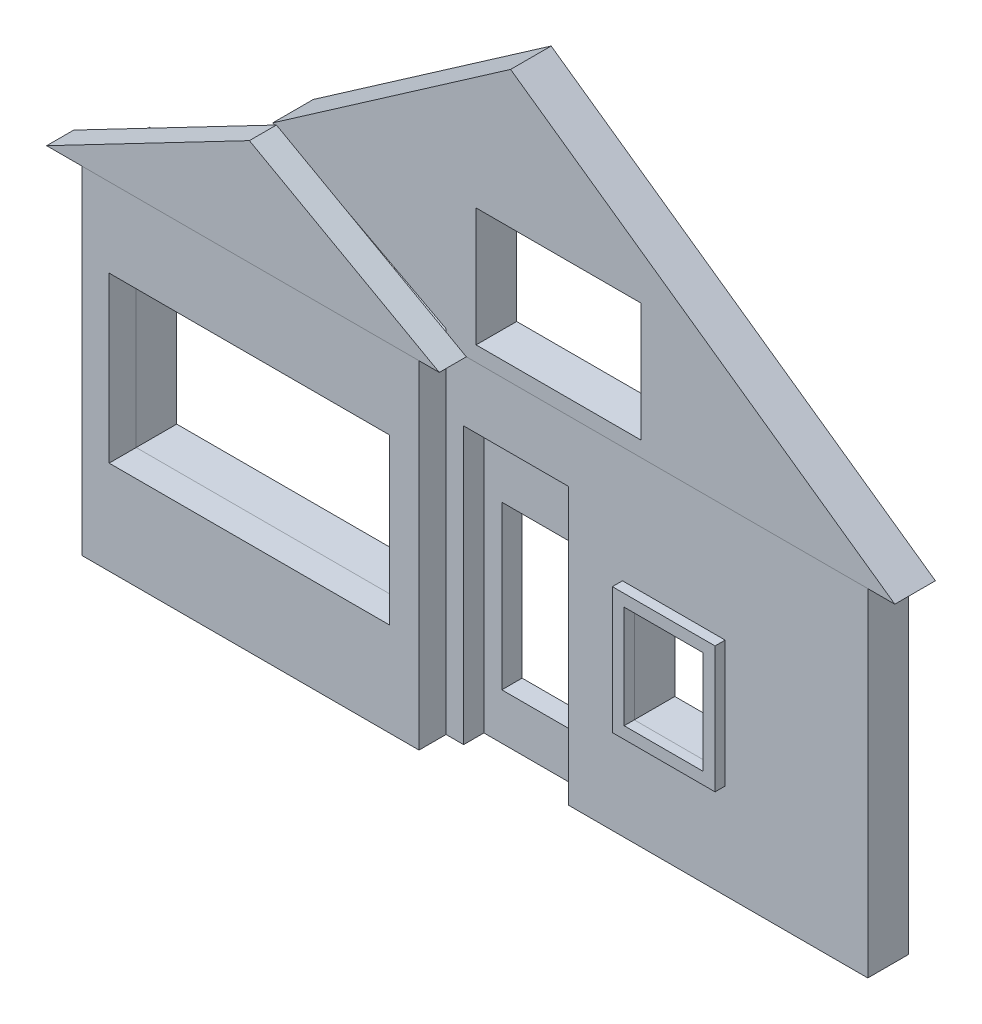
SolidWorks part; units mm, degrees
ref_plane "Front Plane" through (0, 0, 0) normal (0, 0, 1) x (1, 0, 0)
ref_plane "Top Plane" through (0, 0, 0) normal (0, 1, 0) x (1, 0, 0)
ref_plane "Right Plane" through (0, 0, 0) normal (1, 0, 0) x (0, 0, -1)
sketch "WallSketch" plane through (0, 0, 0) normal (0, 0, 1) x (1, 0, 0)
  line L1 (-112.25, -49.9) -> (112.25, -49.9)
  line L2 (-112.25, -49.9) -> (-112.25, 49.9)
  line L3 (-112.25, 49.9) -> (112.25, 49.9)
  line L4 (112.25, -49.9) -> (112.25, 49.9)
  line L5 (-112.25, -49.9) -> (112.25, 49.9) construction
  line L6 (-112.25, 49.9) -> (112.25, -49.9) construction
  point P0 (0, 0)
  dimension "Width" = 224.5
  dimension "Height" = 99.8
extrude "MainWall" add sketch "WallSketch" along normal mid plane 12
sketch "WindowSketch" plane through (0, 0, 6) normal (0, 0, 1) x (1, 0, 0)
  line L1 (43.15, -18.3) -> (66.55, -18.3)
  line L2 (43.15, -18.3) -> (43.15, 12.1)
  line L3 (43.15, 12.1) -> (66.55, 12.1)
  line L4 (66.55, -18.3) -> (66.55, 12.1)
  line L5 (43.15, -18.3) -> (66.55, 12.1) construction
  line L6 (43.15, 12.1) -> (66.55, -18.3) construction
  point P0 (54.85, -3.1)
  dimension "WindowWidth" = 23.4
  dimension "WindowHeight" = 30.4
  dimension "CenterX" = 54.85
  dimension "CenterY" = 3.1
extrude "WindowCut" cut sketch "WindowSketch" against normal blind 12.2
sketch "Pilot001_EntranceRecessSketch" plane through (0, 0, 0) normal (0, 0, 1) x (1, 0, 0)
  line L0 (-7.35, -49.9) -> (23.65, -49.9)
  line L1 (23.65, -49.9) -> (23.65, 31.8)
  line L2 (23.65, 31.8) -> (-7.35, 31.8)
  line L3 (-7.35, 31.8) -> (-7.35, -49.9)
  dimension "L0V0X" = 7.35
  dimension "L0V0Y" = 49.9
  dimension "L0V1X" = 23.65
  dimension "L0V1Y" = 49.9
  dimension "L0V2X" = 23.65
  dimension "L0V2Y" = 31.8
  dimension "L0V3X" = 7.35
  dimension "L0V3Y" = 31.8
extrude "Pilot001_EntranceRecess_PROVISIONAL" cut sketch "Pilot001_EntranceRecessSketch" against normal blind 6 from offset 6
sketch "Pilot001_DoorOpeningSketch" plane through (0, 0, 0) normal (0, 0, 1) x (1, 0, 0)
  line L0 (-2.05, -36.2) -> (18.85, -36.2)
  line L1 (18.85, -36.2) -> (18.85, 11.9)
  line L2 (18.85, 11.9) -> (-2.05, 11.9)
  line L3 (-2.05, 11.9) -> (-2.05, -36.2)
  dimension "L0V0X" = 2.05
  dimension "L0V0Y" = 36.2
  dimension "L0V1X" = 18.85
  dimension "L0V1Y" = 36.2
  dimension "L0V2X" = 18.85
  dimension "L0V2Y" = 11.9
  dimension "L0V3X" = 2.05
  dimension "L0V3Y" = 11.9
extrude "Pilot001_DoorOpening_PROVISIONAL" cut sketch "Pilot001_DoorOpeningSketch" against normal blind 6.2
sketch "Pilot001_LargeWindowOpeningSketch" plane through (0, 0, 0) normal (0, 0, 1) x (1, 0, 0)
  line L0 (-104.25, -22.2) -> (-21.35, -22.2)
  line L1 (-21.35, -22.2) -> (-21.35, 26.5)
  line L2 (-21.35, 26.5) -> (-104.25, 26.5)
  line L3 (-104.25, 26.5) -> (-104.25, -22.2)
  dimension "L0V0X" = 104.25
  dimension "L0V0Y" = 22.2
  dimension "L0V1X" = 21.35
  dimension "L0V1Y" = 22.2
  dimension "L0V2X" = 21.35
  dimension "L0V2Y" = 26.5
  dimension "L0V3X" = 104.25
  dimension "L0V3Y" = 26.5
extrude "Pilot001_LargeWindowOpening_PROVISIONAL" cut sketch "Pilot001_LargeWindowOpeningSketch" against normal blind 12.2 from offset 6
sketch "Pilot001_LeftBayBaseSketch" plane through (0, 0, 0) normal (0, 0, 1) x (1, 0, 0)
  line L0 (-112.25, -49.9) -> (-12.55, -49.9)
  line L1 (-12.55, -49.9) -> (-12.55, -22.2)
  line L2 (-12.55, -22.2) -> (-112.25, -22.2)
  line L3 (-112.25, -22.2) -> (-112.25, -49.9)
  dimension "L0V0Y" = 49.9
  dimension "L0V1Y" = 49.9
  dimension "L0V0X" = 112.25
  dimension "L0V1X" = 12.55
  dimension "L0V2X" = 12.55
  dimension "L0V2Y" = 22.2
  dimension "L0V3X" = 112.25
  dimension "L0V3Y" = 22.2
extrude "Pilot001_LeftBayBase_PROVISIONAL" add sketch "Pilot001_LeftBayBaseSketch" along normal blind 8 from offset 6 separate body
sketch "Pilot001_LeftBayUpperSupportSketch" plane through (0, 0, 0) normal (0, 0, 1) x (1, 0, 0)
  line L0 (-112.25, -22.2) -> (-104.25, -22.2)
  line L1 (-104.25, -22.2) -> (-104.25, 26.5)
  line L2 (-104.25, 26.5) -> (-21.35, 26.5)
  line L3 (-21.35, 26.5) -> (-21.35, -22.2)
  line L4 (-21.35, -22.2) -> (-12.55, -22.2)
  line L5 (-12.55, -22.2) -> (-12.55, 49.9)
  line L6 (-12.55, 49.9) -> (-112.25, 49.9)
  line L7 (-112.25, 49.9) -> (-112.25, -22.2)
  dimension "L0V0Y" = 22.2
  dimension "L0V1Y" = 22.2
  dimension "L0V2Y" = 26.5
  dimension "L0V3Y" = 26.5
  dimension "L0V0X" = 112.25
  dimension "L0V1X" = 104.25
  dimension "L0V2X" = 104.25
  dimension "L0V3X" = 21.35
  dimension "L0V4X" = 21.35
  dimension "L0V4Y" = 22.2
  dimension "L0V5X" = 12.55
  dimension "L0V5Y" = 22.2
  dimension "L0V6X" = 12.55
  dimension "L0V6Y" = 49.9
  dimension "L0V7X" = 112.25
  dimension "L0V7Y" = 49.9
extrude "Pilot001_LeftBayUpperSupport_PROVISIONAL" add sketch "Pilot001_LeftBayUpperSupportSketch" along normal blind 8 from offset 6
sketch "Pilot001_MainGableProfileSketch" plane through (0, 0, 0) normal (0, 0, 1) x (1, 0, 0)
  line L0 (-12.55, 49.9) -> (120.25, 49.9)
  line L1 (120.25, 49.9) -> (6.55, 130.1)
  line L2 (6.55, 130.1) -> (-63.85, 81.2)
  line L3 (-63.85, 81.2) -> (-12.55, 54.1)
  line L4 (-12.55, 54.1) -> (-12.55, 49.9)
  dimension "L0V0Y" = 49.9
  dimension "L0V1Y" = 49.9
  dimension "L0V0X" = 12.55
  dimension "L0V1X" = 120.25
  dimension "L0V2X" = 6.55
  dimension "L0V2Y" = 130.1
  dimension "L0V3X" = 63.85
  dimension "L0V3Y" = 81.2
  dimension "L0V4X" = 12.55
  dimension "L0V4Y" = 54.1
extrude "Pilot001_MainGableProfile_PROVISIONAL" add sketch "Pilot001_MainGableProfileSketch" against normal blind 12 from offset 6 separate body
sketch "Pilot001_LeftGableProfileSketch" plane through (0, 0, 0) normal (0, 0, 1) x (1, 0, 0)
  line L0 (-122.75, 49.9) -> (-6.55, 49.9)
  line L1 (-6.55, 49.9) -> (-62.75, 81.2)
  line L2 (-62.75, 81.2) -> (-122.75, 49.9)
  dimension "L0V0Y" = 49.9
  dimension "L0V1Y" = 49.9
  dimension "L0V0X" = 122.75
  dimension "L0V1X" = 6.55
  dimension "L0V2X" = 62.75
  dimension "L0V2Y" = 81.2
extrude "Pilot001_LeftGableProfile_PROVISIONAL" add sketch "Pilot001_LeftGableProfileSketch" along normal blind 8 from offset 6 separate body
sketch "Pilot001_UpperGableWindowOpeningSketch" plane through (0, 0, 0) normal (0, 0, 1) x (1, 0, 0)
  line L0 (-3.65, 54.4) -> (45.15, 54.4)
  line L1 (45.15, 54.4) -> (45.15, 89.5)
  line L2 (45.15, 89.5) -> (-3.65, 89.5)
  line L3 (-3.65, 89.5) -> (-3.65, 54.4)
  dimension "L0V0X" = 3.65
  dimension "L0V0Y" = 54.4
  dimension "L0V1X" = 45.15
  dimension "L0V1Y" = 54.4
  dimension "L0V2X" = 45.15
  dimension "L0V2Y" = 89.5
  dimension "L0V3X" = 3.65
  dimension "L0V3Y" = 89.5
extrude "Pilot001_UpperGableWindowOpening_PROVISIONAL" cut sketch "Pilot001_UpperGableWindowOpeningSketch" against normal blind 12.2 from offset 6
sketch "Pilot001_OpeningSurroundSketch" plane through (0, 0, 0) normal (0, 0, 1) x (1, 0, 0)
  line L0 (39.65, -21.8) -> (70.05, -21.8)
  line L1 (70.05, -21.8) -> (70.05, 15.6)
  line L2 (70.05, 15.6) -> (39.65, 15.6)
  line L3 (39.65, 15.6) -> (39.65, -21.8)
  line L4 (43.15, -18.3) -> (66.55, -18.3)
  line L5 (66.55, -18.3) -> (66.55, 12.1)
  line L6 (66.55, 12.1) -> (43.15, 12.1)
  line L7 (43.15, 12.1) -> (43.15, -18.3)
  dimension "L0V0X" = 39.65
  dimension "L0V0Y" = 21.8
  dimension "L0V1X" = 70.05
  dimension "L0V1Y" = 21.8
  dimension "L0V2X" = 70.05
  dimension "L0V2Y" = 15.6
  dimension "L0V3X" = 39.65
  dimension "L0V3Y" = 15.6
  dimension "L1V0X" = 43.15
  dimension "L1V0Y" = 18.3
  dimension "L1V1X" = 66.55
  dimension "L1V1Y" = 18.3
  dimension "L1V2X" = 66.55
  dimension "L1V2Y" = 12.1
  dimension "L1V3X" = 43.15
  dimension "L1V3Y" = 12.1
extrude "Pilot001_OpeningSurround_PROVISIONAL" add sketch "Pilot001_OpeningSurroundSketch" along normal blind 3 from offset 6 separate body
equation "\"FacadeWidth\" = 224.5mm"
equation "\"WallHeight\" = 99.8mm"
equation "\"BackingThickness\" = 12mm"
equation "\"ArchitecturalHeight\" = 180mm"
equation "\"BayWidth\" = 99.7mm"
equation "\"BaseHeight\" = 27.7mm"
equation "\"BayProjection\" = 8mm"
equation "\"LargeLeft\" = 8mm"
equation "\"LargeRight\" = 90.9mm"
equation "\"LargeHead\" = 76.4mm"
equation "\"EntranceLeft\" = 104.9mm"
equation "\"EntranceRight\" = 135.9mm"
equation "\"EntranceHead\" = 81.7mm"
equation "\"RecessDepth\" = 6mm"
equation "\"DoorLeft\" = 110.2mm"
equation "\"DoorRight\" = 131.1mm"
equation "\"DoorBottom\" = 13.7mm"
equation "\"DoorHead\" = 61.8mm"
equation "\"RightLeft\" = 155.4mm"
equation "\"RightRight\" = 178.8mm"
equation "\"RightBottom\" = 31.6mm"
equation "\"RightHead\" = 62mm"
equation "\"UpperLeft\" = 108.6mm"
equation "\"UpperRight\" = 157.4mm"
equation "\"UpperBottom\" = 104.3mm"
equation "\"UpperHead\" = 139.4mm"
equation "\"BorderLeft\" = 3.5mm"
equation "\"BorderRight\" = 3.5mm"
equation "\"BorderTop\" = 3.5mm"
equation "\"BorderBottom\" = 3.5mm"
equation "\"SurroundProjection\" = 3mm"
equation "\"MainRoofRight\" = 232.5mm"
equation "\"MainRidgeX\" = 118.8mm"
equation "\"RoofJunctionX\" = 48.4mm"
equation "\"LowerRidge\" = 131.1mm"
equation "\"RoofJunctionY\" = 104mm"
equation "\"LeftRoofLeft\" = -10.5mm"
equation "\"LeftRoofRight\" = 105.7mm"
equation "\"LeftRidgeX\" = 49.5mm"
equation "\"CutTolerance\" = 0.2mm"
equation "\"Width@WallSketch\" = \"FacadeWidth\""
equation "\"Height@WallSketch\" = \"WallHeight\""
equation "\"D1@MainWall\" = \"BackingThickness\""
equation "\"WindowWidth@WindowSketch\" = \"RightRight\" - \"RightLeft\""
equation "\"WindowHeight@WindowSketch\" = \"RightHead\" - \"RightBottom\""
equation "\"CenterX@WindowSketch\" = abs((\"RightLeft\" + \"RightRight\") / 2 - \"FacadeWidth\" / 2)"
equation "\"CenterY@WindowSketch\" = abs((\"RightBottom\" + \"RightHead\") / 2 - \"WallHeight\" / 2)"
equation "\"L0V0X@Pilot001_EntranceRecessSketch\" = abs((\"EntranceLeft\"-(\"FacadeWidth\"/2)))"
equation "\"L0V0Y@Pilot001_EntranceRecessSketch\" = abs((0mm-(\"WallHeight\"/2)))"
equation "\"L0V1X@Pilot001_EntranceRecessSketch\" = abs((\"EntranceRight\"-(\"FacadeWidth\"/2)))"
equation "\"L0V1Y@Pilot001_EntranceRecessSketch\" = abs((0mm-(\"WallHeight\"/2)))"
equation "\"L0V2X@Pilot001_EntranceRecessSketch\" = abs((\"EntranceRight\"-(\"FacadeWidth\"/2)))"
equation "\"L0V2Y@Pilot001_EntranceRecessSketch\" = abs((\"EntranceHead\"-(\"WallHeight\"/2)))"
equation "\"L0V3X@Pilot001_EntranceRecessSketch\" = abs((\"EntranceLeft\"-(\"FacadeWidth\"/2)))"
equation "\"L0V3Y@Pilot001_EntranceRecessSketch\" = abs((\"EntranceHead\"-(\"WallHeight\"/2)))"
equation "\"Depth@Pilot001_EntranceRecess_PROVISIONAL\" = \"RecessDepth\""
equation "\"L0V0X@Pilot001_DoorOpeningSketch\" = abs((\"DoorLeft\"-(\"FacadeWidth\"/2)))"
equation "\"L0V0Y@Pilot001_DoorOpeningSketch\" = abs((\"DoorBottom\"-(\"WallHeight\"/2)))"
equation "\"L0V1X@Pilot001_DoorOpeningSketch\" = abs((\"DoorRight\"-(\"FacadeWidth\"/2)))"
equation "\"L0V1Y@Pilot001_DoorOpeningSketch\" = abs((\"DoorBottom\"-(\"WallHeight\"/2)))"
equation "\"L0V2X@Pilot001_DoorOpeningSketch\" = abs((\"DoorRight\"-(\"FacadeWidth\"/2)))"
equation "\"L0V2Y@Pilot001_DoorOpeningSketch\" = abs((\"DoorHead\"-(\"WallHeight\"/2)))"
equation "\"L0V3X@Pilot001_DoorOpeningSketch\" = abs((\"DoorLeft\"-(\"FacadeWidth\"/2)))"
equation "\"L0V3Y@Pilot001_DoorOpeningSketch\" = abs((\"DoorHead\"-(\"WallHeight\"/2)))"
equation "\"Depth@Pilot001_DoorOpening_PROVISIONAL\" = ((\"BackingThickness\"-\"RecessDepth\")+\"CutTolerance\")"
equation "\"L0V0X@Pilot001_LargeWindowOpeningSketch\" = abs((\"LargeLeft\"-(\"FacadeWidth\"/2)))"
equation "\"L0V0Y@Pilot001_LargeWindowOpeningSketch\" = abs((\"BaseHeight\"-(\"WallHeight\"/2)))"
equation "\"L0V1X@Pilot001_LargeWindowOpeningSketch\" = abs((\"LargeRight\"-(\"FacadeWidth\"/2)))"
equation "\"L0V1Y@Pilot001_LargeWindowOpeningSketch\" = abs((\"BaseHeight\"-(\"WallHeight\"/2)))"
equation "\"L0V2X@Pilot001_LargeWindowOpeningSketch\" = abs((\"LargeRight\"-(\"FacadeWidth\"/2)))"
equation "\"L0V2Y@Pilot001_LargeWindowOpeningSketch\" = abs((\"LargeHead\"-(\"WallHeight\"/2)))"
equation "\"L0V3X@Pilot001_LargeWindowOpeningSketch\" = abs((\"LargeLeft\"-(\"FacadeWidth\"/2)))"
equation "\"L0V3Y@Pilot001_LargeWindowOpeningSketch\" = abs((\"LargeHead\"-(\"WallHeight\"/2)))"
equation "\"Depth@Pilot001_LargeWindowOpening_PROVISIONAL\" = (\"BackingThickness\"+\"CutTolerance\")"
equation "\"L0V0X@Pilot001_LeftBayBaseSketch\" = abs((0mm-(\"FacadeWidth\"/2)))"
equation "\"L0V0Y@Pilot001_LeftBayBaseSketch\" = abs((0mm-(\"WallHeight\"/2)))"
equation "\"L0V1X@Pilot001_LeftBayBaseSketch\" = abs((\"BayWidth\"-(\"FacadeWidth\"/2)))"
equation "\"L0V1Y@Pilot001_LeftBayBaseSketch\" = abs((0mm-(\"WallHeight\"/2)))"
equation "\"L0V2X@Pilot001_LeftBayBaseSketch\" = abs((\"BayWidth\"-(\"FacadeWidth\"/2)))"
equation "\"L0V2Y@Pilot001_LeftBayBaseSketch\" = abs((\"BaseHeight\"-(\"WallHeight\"/2)))"
equation "\"L0V3X@Pilot001_LeftBayBaseSketch\" = abs((0mm-(\"FacadeWidth\"/2)))"
equation "\"L0V3Y@Pilot001_LeftBayBaseSketch\" = abs((\"BaseHeight\"-(\"WallHeight\"/2)))"
equation "\"Depth@Pilot001_LeftBayBase_PROVISIONAL\" = \"BayProjection\""
equation "\"L0V0X@Pilot001_LeftBayUpperSupportSketch\" = abs((0mm-(\"FacadeWidth\"/2)))"
equation "\"L0V0Y@Pilot001_LeftBayUpperSupportSketch\" = abs((\"BaseHeight\"-(\"WallHeight\"/2)))"
equation "\"L0V1X@Pilot001_LeftBayUpperSupportSketch\" = abs((\"LargeLeft\"-(\"FacadeWidth\"/2)))"
equation "\"L0V1Y@Pilot001_LeftBayUpperSupportSketch\" = abs((\"BaseHeight\"-(\"WallHeight\"/2)))"
equation "\"L0V2X@Pilot001_LeftBayUpperSupportSketch\" = abs((\"LargeLeft\"-(\"FacadeWidth\"/2)))"
equation "\"L0V2Y@Pilot001_LeftBayUpperSupportSketch\" = abs((\"LargeHead\"-(\"WallHeight\"/2)))"
equation "\"L0V3X@Pilot001_LeftBayUpperSupportSketch\" = abs((\"LargeRight\"-(\"FacadeWidth\"/2)))"
equation "\"L0V3Y@Pilot001_LeftBayUpperSupportSketch\" = abs((\"LargeHead\"-(\"WallHeight\"/2)))"
equation "\"L0V4X@Pilot001_LeftBayUpperSupportSketch\" = abs((\"LargeRight\"-(\"FacadeWidth\"/2)))"
equation "\"L0V4Y@Pilot001_LeftBayUpperSupportSketch\" = abs((\"BaseHeight\"-(\"WallHeight\"/2)))"
equation "\"L0V5X@Pilot001_LeftBayUpperSupportSketch\" = abs((\"BayWidth\"-(\"FacadeWidth\"/2)))"
equation "\"L0V5Y@Pilot001_LeftBayUpperSupportSketch\" = abs((\"BaseHeight\"-(\"WallHeight\"/2)))"
equation "\"L0V6X@Pilot001_LeftBayUpperSupportSketch\" = abs((\"BayWidth\"-(\"FacadeWidth\"/2)))"
equation "\"L0V6Y@Pilot001_LeftBayUpperSupportSketch\" = abs((\"WallHeight\"-(\"WallHeight\"/2)))"
equation "\"L0V7X@Pilot001_LeftBayUpperSupportSketch\" = abs((0mm-(\"FacadeWidth\"/2)))"
equation "\"L0V7Y@Pilot001_LeftBayUpperSupportSketch\" = abs((\"WallHeight\"-(\"WallHeight\"/2)))"
equation "\"Depth@Pilot001_LeftBayUpperSupport_PROVISIONAL\" = \"BayProjection\""
equation "\"L0V0X@Pilot001_MainGableProfileSketch\" = abs((\"BayWidth\"-(\"FacadeWidth\"/2)))"
equation "\"L0V0Y@Pilot001_MainGableProfileSketch\" = abs((\"WallHeight\"-(\"WallHeight\"/2)))"
equation "\"L0V1X@Pilot001_MainGableProfileSketch\" = abs((\"MainRoofRight\"-(\"FacadeWidth\"/2)))"
equation "\"L0V1Y@Pilot001_MainGableProfileSketch\" = abs((\"WallHeight\"-(\"WallHeight\"/2)))"
equation "\"L0V2X@Pilot001_MainGableProfileSketch\" = abs((\"MainRidgeX\"-(\"FacadeWidth\"/2)))"
equation "\"L0V2Y@Pilot001_MainGableProfileSketch\" = abs((\"ArchitecturalHeight\"-(\"WallHeight\"/2)))"
equation "\"L0V3X@Pilot001_MainGableProfileSketch\" = abs((\"RoofJunctionX\"-(\"FacadeWidth\"/2)))"
equation "\"L0V3Y@Pilot001_MainGableProfileSketch\" = abs((\"LowerRidge\"-(\"WallHeight\"/2)))"
equation "\"L0V4X@Pilot001_MainGableProfileSketch\" = abs((\"BayWidth\"-(\"FacadeWidth\"/2)))"
equation "\"L0V4Y@Pilot001_MainGableProfileSketch\" = abs((\"RoofJunctionY\"-(\"WallHeight\"/2)))"
equation "\"Depth@Pilot001_MainGableProfile_PROVISIONAL\" = \"BackingThickness\""
equation "\"L0V0X@Pilot001_LeftGableProfileSketch\" = abs((\"LeftRoofLeft\"-(\"FacadeWidth\"/2)))"
equation "\"L0V0Y@Pilot001_LeftGableProfileSketch\" = abs((\"WallHeight\"-(\"WallHeight\"/2)))"
equation "\"L0V1X@Pilot001_LeftGableProfileSketch\" = abs((\"LeftRoofRight\"-(\"FacadeWidth\"/2)))"
equation "\"L0V1Y@Pilot001_LeftGableProfileSketch\" = abs((\"WallHeight\"-(\"WallHeight\"/2)))"
equation "\"L0V2X@Pilot001_LeftGableProfileSketch\" = abs((\"LeftRidgeX\"-(\"FacadeWidth\"/2)))"
equation "\"L0V2Y@Pilot001_LeftGableProfileSketch\" = abs((\"LowerRidge\"-(\"WallHeight\"/2)))"
equation "\"Depth@Pilot001_LeftGableProfile_PROVISIONAL\" = \"BayProjection\""
equation "\"L0V0X@Pilot001_UpperGableWindowOpeningSketch\" = abs((\"UpperLeft\"-(\"FacadeWidth\"/2)))"
equation "\"L0V0Y@Pilot001_UpperGableWindowOpeningSketch\" = abs((\"UpperBottom\"-(\"WallHeight\"/2)))"
equation "\"L0V1X@Pilot001_UpperGableWindowOpeningSketch\" = abs((\"UpperRight\"-(\"FacadeWidth\"/2)))"
equation "\"L0V1Y@Pilot001_UpperGableWindowOpeningSketch\" = abs((\"UpperBottom\"-(\"WallHeight\"/2)))"
equation "\"L0V2X@Pilot001_UpperGableWindowOpeningSketch\" = abs((\"UpperRight\"-(\"FacadeWidth\"/2)))"
equation "\"L0V2Y@Pilot001_UpperGableWindowOpeningSketch\" = abs((\"UpperHead\"-(\"WallHeight\"/2)))"
equation "\"L0V3X@Pilot001_UpperGableWindowOpeningSketch\" = abs((\"UpperLeft\"-(\"FacadeWidth\"/2)))"
equation "\"L0V3Y@Pilot001_UpperGableWindowOpeningSketch\" = abs((\"UpperHead\"-(\"WallHeight\"/2)))"
equation "\"Depth@Pilot001_UpperGableWindowOpening_PROVISIONAL\" = (\"BackingThickness\"+\"CutTolerance\")"
equation "\"L0V0X@Pilot001_OpeningSurroundSketch\" = abs(((\"RightLeft\"-\"BorderLeft\")-(\"FacadeWidth\"/2)))"
equation "\"L0V0Y@Pilot001_OpeningSurroundSketch\" = abs(((\"RightBottom\"-\"BorderBottom\")-(\"WallHeight\"/2)))"
equation "\"L0V1X@Pilot001_OpeningSurroundSketch\" = abs(((\"RightRight\"+\"BorderRight\")-(\"FacadeWidth\"/2)))"
equation "\"L0V1Y@Pilot001_OpeningSurroundSketch\" = abs(((\"RightBottom\"-\"BorderBottom\")-(\"WallHeight\"/2)))"
equation "\"L0V2X@Pilot001_OpeningSurroundSketch\" = abs(((\"RightRight\"+\"BorderRight\")-(\"FacadeWidth\"/2)))"
equation "\"L0V2Y@Pilot001_OpeningSurroundSketch\" = abs(((\"RightHead\"+\"BorderTop\")-(\"WallHeight\"/2)))"
equation "\"L0V3X@Pilot001_OpeningSurroundSketch\" = abs(((\"RightLeft\"-\"BorderLeft\")-(\"FacadeWidth\"/2)))"
equation "\"L0V3Y@Pilot001_OpeningSurroundSketch\" = abs(((\"RightHead\"+\"BorderTop\")-(\"WallHeight\"/2)))"
equation "\"L1V0X@Pilot001_OpeningSurroundSketch\" = abs((\"RightLeft\"-(\"FacadeWidth\"/2)))"
equation "\"L1V0Y@Pilot001_OpeningSurroundSketch\" = abs((\"RightBottom\"-(\"WallHeight\"/2)))"
equation "\"L1V1X@Pilot001_OpeningSurroundSketch\" = abs((\"RightRight\"-(\"FacadeWidth\"/2)))"
equation "\"L1V1Y@Pilot001_OpeningSurroundSketch\" = abs((\"RightBottom\"-(\"WallHeight\"/2)))"
equation "\"L1V2X@Pilot001_OpeningSurroundSketch\" = abs((\"RightRight\"-(\"FacadeWidth\"/2)))"
equation "\"L1V2Y@Pilot001_OpeningSurroundSketch\" = abs((\"RightHead\"-(\"WallHeight\"/2)))"
equation "\"L1V3X@Pilot001_OpeningSurroundSketch\" = abs((\"RightLeft\"-(\"FacadeWidth\"/2)))"
equation "\"L1V3Y@Pilot001_OpeningSurroundSketch\" = abs((\"RightHead\"-(\"WallHeight\"/2)))"
equation "\"Depth@Pilot001_OpeningSurround_PROVISIONAL\" = \"SurroundProjection\""
